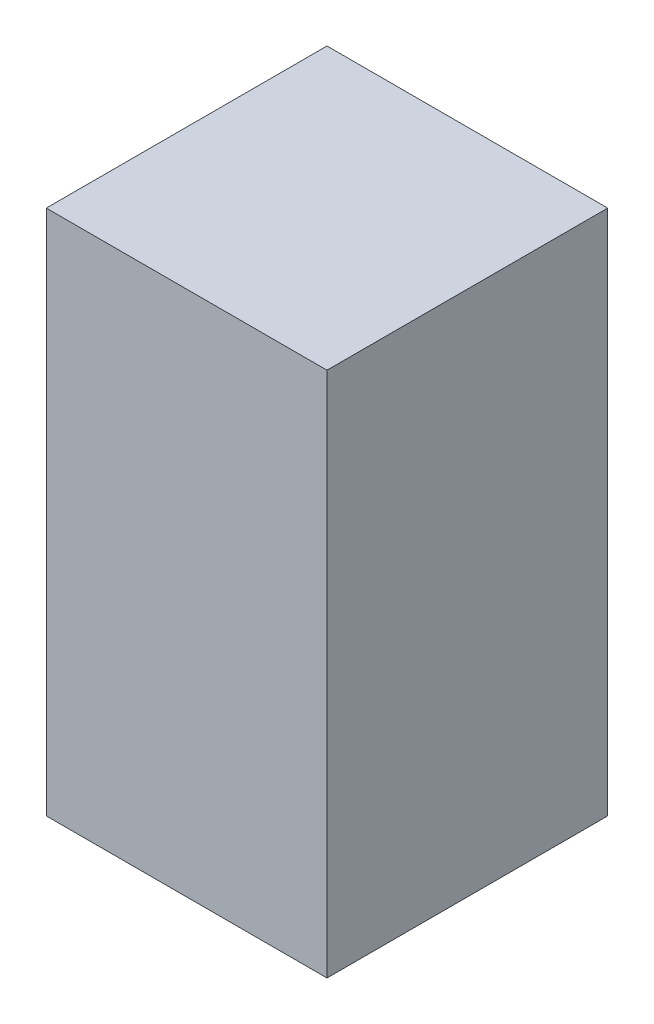
SolidWorks part; units mm, degrees
ref_plane "Front Plane" through (0, 0, 0) normal (0, 0, 1) x (1, 0, 0)
ref_plane "Top Plane" through (0, 0, 0) normal (0, 1, 0) x (1, 0, 0)
ref_plane "Right Plane" through (0, 0, 0) normal (1, 0, 0) x (0, 0, -1)
sketch "Sketch1" plane through (0, 0, 0) normal (0, 1, 0) x (1, 0, 0)
  line L1 (0, 34.4305) -> (50.8, 34.4305)
  line L2 (0, 34.4305) -> (0, -16.3695)
  line L3 (0, -16.3695) -> (50.8, -16.3695)
  line L4 (50.8, 34.4305) -> (50.8, -16.3695)
  dimension "D1" = 50.8
extrude "Boss-Extrude2" add sketch "Sketch1" along normal blind 95.25
